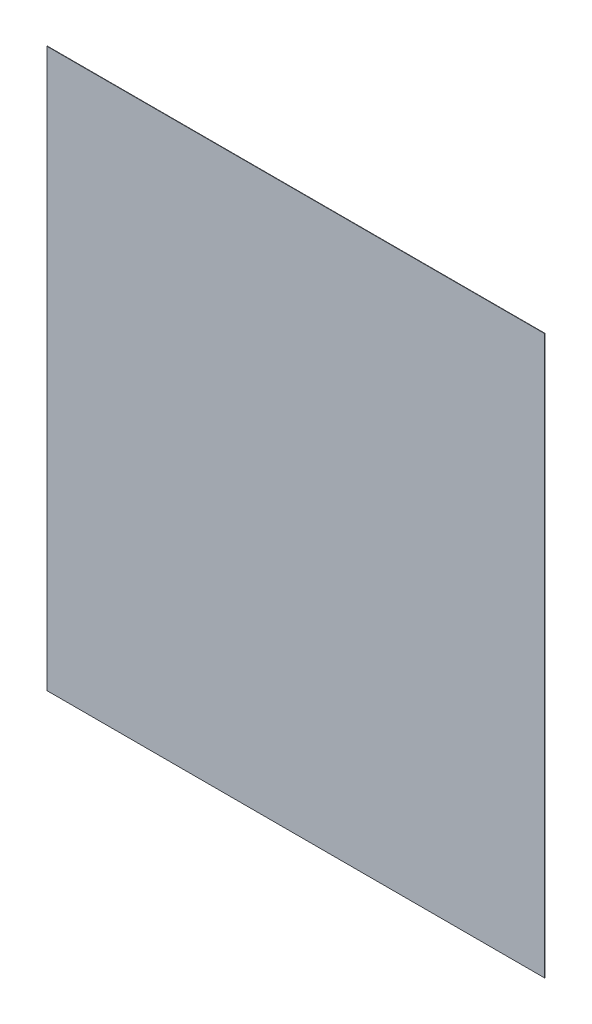
SolidWorks part; units mm, degrees
ref_plane "Front Plane" through (0, 0, 0) normal (0, 0, 1) x (1, 0, 0)
ref_plane "Top Plane" through (0, 0, 0) normal (0, 1, 0) x (1, 0, 0)
ref_plane "Right Plane" through (0, 0, 0) normal (1, 0, 0) x (0, 0, -1)
other "Configuration Table"
sketch "Sketch1" plane through (0, 0, 0) normal (0, 0, 1) x (1, 0, 0)
  line L1 (62.5, 181.5) -> (1337.5, 181.5)
  line L2 (62.5, 181.5) -> (62.5, 1611)
  line L3 (62.5, 1611) -> (1337.5, 1611)
  line L4 (1337.5, 181.5) -> (1337.5, 1611)
extrude "STORE_ic_arka_1" add sketch "Sketch1" against normal blind 1 from offset 757.5 separate body
